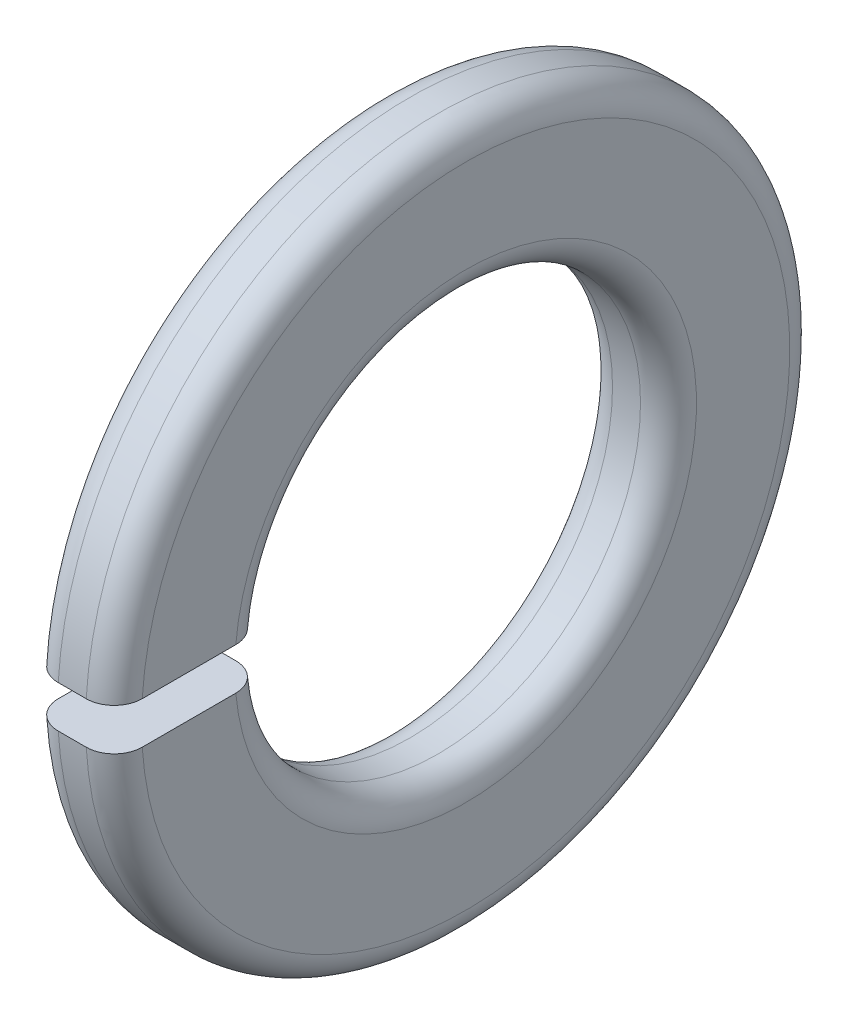
SolidWorks part; units mm, degrees
ref_plane "Plane1" through (0, 0, 0) normal (0, 0, 1) x (1, 0, 0)
ref_plane "Plane2" through (0, 0, 0) normal (0, 1, 0) x (1, 0, 0)
ref_plane "Plane3" through (0, 0, 0) normal (1, 0, 0) x (0, 0, -1)
sketch "Sketch1" plane through (0, 0, 0) normal (0, 0, 1) x (1, 0, 0)
  line L0 (-34.925, 0) -> (9.525, 0) construction
  line L1 (0, 2.475) -> (0, 3.475)
  line L2 (-0.3, 3.775) -> (-0.6, 3.775)
  line L3 (-0.9, 3.475) -> (-0.9, 2.475)
  line L4 (-0.6, 2.175) -> (-0.3, 2.175)
  arc A0 (-0.6, 2.175) -> (-0.9, 2.475) centre (-0.6, 2.475) cw
  arc A1 (0, 2.475) -> (-0.3, 2.175) centre (-0.3, 2.475) cw
  arc A2 (0, 3.475) -> (-0.3, 3.775) centre (-0.3, 3.475) ccw
  arc A3 (-0.6, 3.775) -> (-0.9, 3.475) centre (-0.6, 3.475) ccw
  point P8 (-0.9, 2.175)
  point P14 (0, 3.775)
  point P17 (-0.9, 3.775)
  dimension "Fillet_rad" = 0.3
  dimension "Thickness" = 0.9
  dimension "Inside_dia" = 4.35
  dimension "Outside_dia" = 7.55
revolve "Base-Revolve" add sketch "Sketch1" angle 360 about L0
sketch "Sketch2" plane through (0, 0, 0) normal (-1, 0, 0) x (0, -1, 0)
  line L0 (-0.225, 0) -> (0.225, 0)
  line L1 (0, 0) -> (0, 12.7) construction
  line L2 (0.225, 0) -> (0.225, 3.8505)
  line L3 (0.225, 3.8505) -> (-0.225, 3.8505)
  line L4 (-0.225, 3.8505) -> (-0.225, 0)
  dimension "D1" = 0.45
  dimension "D2" = 3.8505
extrude "Gap" cut sketch "Sketch2" along normal through all
equation "\"D1@Sketch2\" = \"Thickness@Sketch1\" * 0.5"
equation "\"D2@Sketch2\" = \"Outside_dia@Sketch1\" * 0.51"
